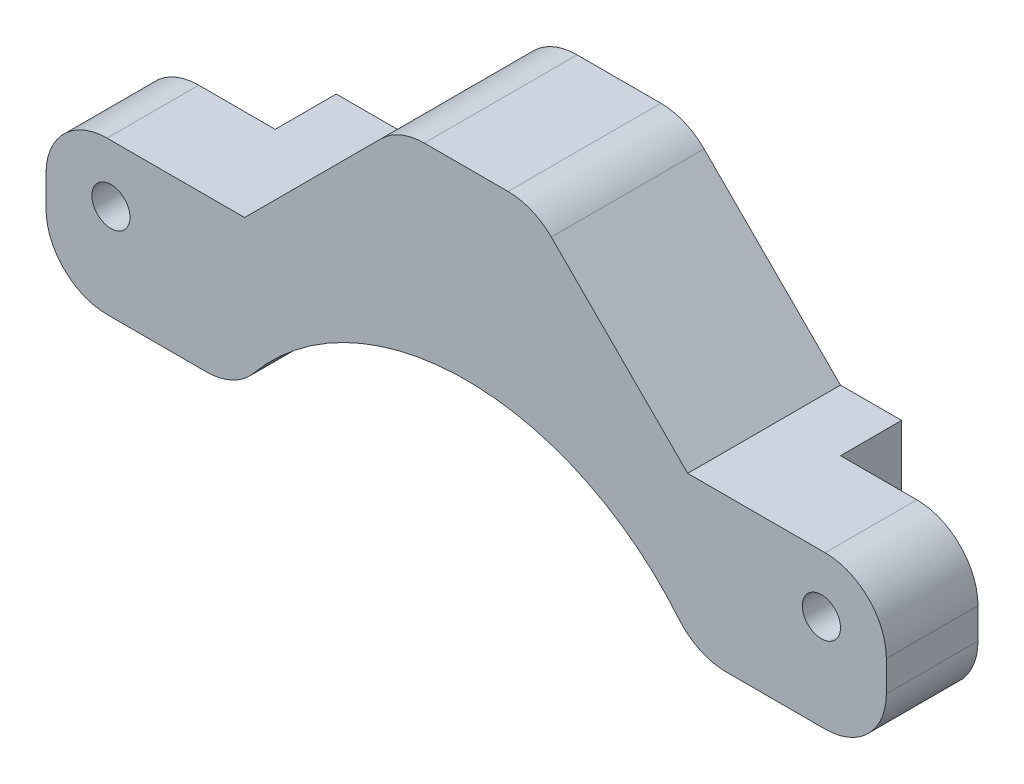
SolidWorks part; units mm, degrees
ref_plane "Alzado" through (0, 0, 0) normal (0, 0, 1) x (1, 0, 0)
ref_plane "Planta" through (0, 0, 0) normal (0, 1, 0) x (1, 0, 0)
ref_plane "Vista lateral" through (0, 0, 0) normal (1, 0, 0) x (0, 0, -1)
sketch "Croquis1" plane through (0, 0, 0) normal (0, 0, 1) x (1, 0, 0)
  line L0 (-68.8373, 14.25) -> (-55.8373, 14.25)
  line L2 (-68.8373, 14.25) -> (-68.8373, 4.25)
  line L4 (-13.8373, 14.25) -> (-13.8373, 4.25)
  line L5 (-55.8373, 14.25) -> (-45.7373, 24.35)
  line L6 (-13.8373, 14.25) -> (-26.8373, 14.25)
  line L7 (-26.8373, 14.25) -> (-36.9373, 24.35)
  line L8 (-36.9373, 24.35) -> (-45.7373, 24.35)
  line L9 (-41.3373, 4.25) -> (-26.3373, 4.25) construction
  line L10 (-26.3373, 4.25) -> (-56.3373, 4.25) construction
  line L11 (-13.8373, 4.25) -> (-26.3373, 4.25)
  line L12 (-56.3373, 4.25) -> (-68.8373, 4.25)
  circle A0 centre (-18.0873, 10.5) radius 1.25
  circle A1 centre (-64.5873, 10.5) radius 1.25
  arc A2 (-56.3373, 4.25) -> (-26.3373, 4.25) centre (-41.3373, -5.7174) cw
  dimension "D4" = 2.5
  dimension "D5" = 2.5
  dimension "D9" = 15
  dimension "D1" = 55
  dimension "D2" = 10
  dimension "D6" = 46.5
  dimension "D7" = 4.25
  dimension "D8" = 30
extrude "Saliente-Extruir1" add sketch "Croquis1" along normal blind 10
sketch "Croquis2" plane through (0, 0, 0) normal (0, 0, -1) x (-1, 0, 0)
  line L0 (55.8373, 14.25) -> (68.8373, 14.25) construction
  line L1 (68.8373, 4.25) -> (59.8373, 4.25)
  line L2 (68.8373, 4.25) -> (68.8373, 14.25)
  line L3 (68.8373, 14.25) -> (59.8373, 14.25)
  line L4 (59.8373, 4.25) -> (59.8373, 14.25)
  line L5 (13.8373, 14.25) -> (26.8373, 14.25) construction
  line L6 (13.8373, 4.25) -> (22.8373, 4.25)
  line L7 (13.8373, 4.25) -> (13.8373, 14.25)
  line L8 (13.8373, 14.25) -> (22.8373, 14.25)
  line L9 (22.8373, 4.25) -> (22.8373, 14.25)
  dimension "D1" = 9
  dimension "D2" = 9
extrude "Cortar-Extruir1" cut sketch "Croquis2" against normal blind 4
sketch "Croquis3" plane through (0, 0, 4) normal (0, 0, -1) x (-1, 0, 0)
  line L1 (62.1047, 10.5) -> (63.346, 8.35)
  line L2 (63.346, 8.35) -> (65.8286, 8.35)
  line L3 (65.8286, 8.35) -> (67.0699, 10.5)
  line L4 (67.0699, 10.5) -> (65.8286, 12.65)
  line L5 (65.8286, 12.65) -> (63.346, 12.65)
  line L6 (63.346, 12.65) -> (62.1047, 10.5)
  line L7 (15.6047, 10.5) -> (16.846, 8.35)
  line L8 (16.846, 8.35) -> (19.3286, 8.35)
  line L9 (19.3286, 8.35) -> (20.5699, 10.5)
  line L10 (20.5699, 10.5) -> (19.3286, 12.65)
  line L11 (19.3286, 12.65) -> (16.846, 12.65)
  line L12 (16.846, 12.65) -> (15.6047, 10.5)
  circle A0 centre (64.5873, 10.5) radius 2.15 construction
  circle A1 centre (18.0873, 10.5) radius 2.15 construction
  dimension "D1" = 4.3
  dimension "D2" = 4.3
extrude "Cortar-Extruir2" cut sketch "Croquis3" against normal blind 1.5
fillet "Redondeo2" radius 4 8 edges at (-56.3373, 4.25, 5) (-26.3373, 4.25, 5) (-13.8373, 4.25, 7) (-13.8373, 14.25, 7) (-36.9373, 24.35, 5) (-45.7373, 24.35, 5) (-68.8373, 4.25, 7) (-68.8373, 14.25, 7)
